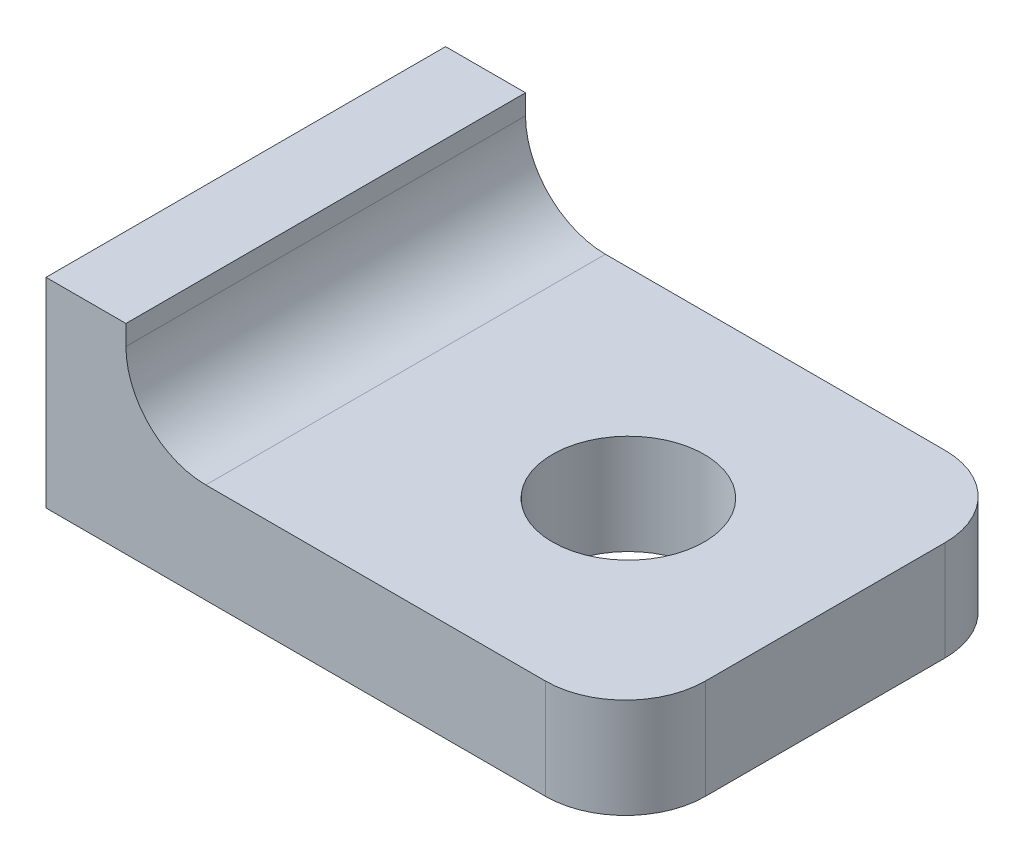
SolidWorks part; units mm, degrees
ref_plane "Front Plane" through (0, 0, 0) normal (0, 0, 1) x (1, 0, 0)
ref_plane "Top Plane" through (0, 0, 0) normal (0, 1, 0) x (1, 0, 0)
ref_plane "Right Plane" through (0, 0, 0) normal (1, 0, 0) x (0, 0, -1)
sketch "Sketch1" plane through (0, 0, 0) normal (0, 1, 0) x (1, 0, 0)
  line L1 (-7.25, 5) -> (7.25, 5)
  line L2 (-7.25, 5) -> (-7.25, -5)
  line L3 (-7.25, -5) -> (7.25, -5)
  line L4 (7.25, 5) -> (7.25, -5)
  line L5 (-7.25, 5) -> (7.25, -5) construction
  line L6 (-7.25, -5) -> (7.25, 5) construction
  point P0 (0, 0)
  dimension "D1" = 14.5
  dimension "D2" = 10
extrude "Boss-Extrude1" add sketch "Sketch1" along normal blind 2.5
sketch "Sketch2" plane through (0, 2.5, 0) normal (0, 1, 0) x (1, 0, 0)
  circle A0 centre (2.3235, 0) radius 1.9
extrude "Cut-Extrude1" cut sketch "Sketch2" against normal through all
sketch "Sketch3" plane through (0, 2.5, 0) normal (0, 1, 0) x (1, 0, 0)
  line L0 (-7.25, -5) -> (7.25, -5) construction
  line L1 (-7.25, 5) -> (-5.25, 5)
  line L2 (-7.25, 5) -> (-7.25, -5)
  line L3 (-7.25, -5) -> (-5.25, -5)
  line L4 (-5.25, 5) -> (-5.25, -5)
  dimension "D1" = 2
extrude "Boss-Extrude2" add sketch "Sketch3" along normal blind 2.5
fillet "Fillet1" radius 2 1 edges at (-5.25, 2.5, 0)
fillet "Fillet2" radius 2 2 edges at (7.25, 1.25, -5) (7.25, 1.25, 5)
